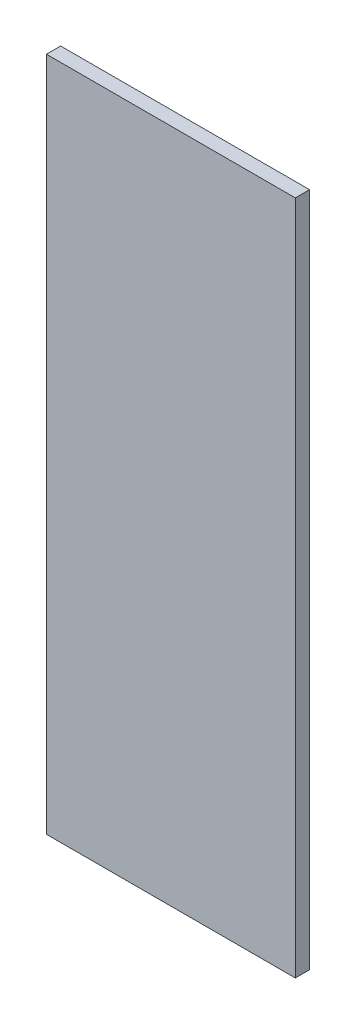
SolidWorks part; units mm, degrees
material "STYCAST 2850FT/Catalyst 23LV"
ref_plane "Front Plane" through (0, 0, 0) normal (0, 0, 1) x (1, 0, 0)
ref_plane "Top Plane" through (0, 0, 0) normal (0, 1, 0) x (1, 0, 0)
ref_plane "Right Plane" through (0, 0, 0) normal (1, 0, 0) x (0, 0, -1)
sketch "Sketch1" plane through (0, 0, 0) normal (0, 0, 1) x (1, 0, 0)
  line L1 (0, 0) -> (3.5, 0)
  line L2 (0, 0) -> (0, 9.5)
  line L3 (0, 9.5) -> (3.5, 9.5)
  line L4 (3.5, 0) -> (3.5, 9.5)
  dimension "D1" = 3.5
  dimension "D2" = 9.5
extrude "Boss-Extrude1" add sketch "Sketch1" along normal blind 0.2
